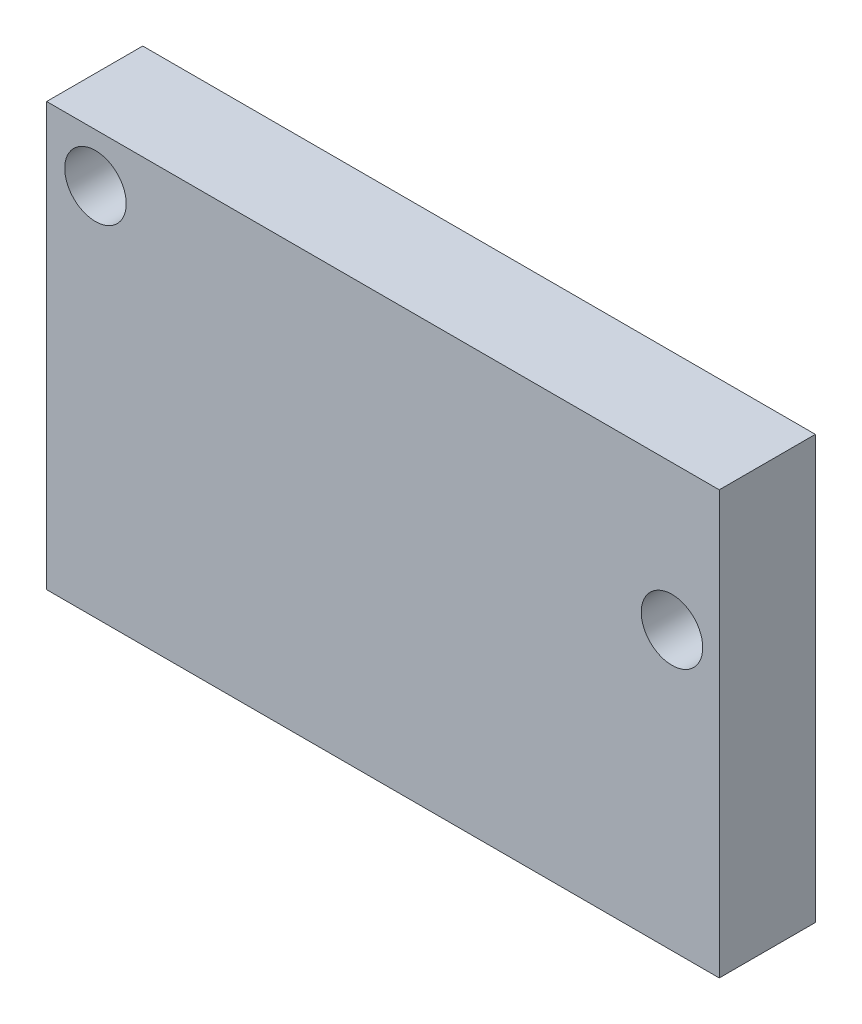
SolidWorks part; units mm, degrees
ref_plane "前视基准面" through (0, 0, 0) normal (0, 0, 1) x (1, 0, 0)
ref_plane "上视基准面" through (0, 0, 0) normal (0, 1, 0) x (1, 0, 0)
ref_plane "右视基准面" through (0, 0, 0) normal (1, 0, 0) x (0, 0, -1)
other "Configuration Table"
sketch "草图1" plane through (0, 0, 0) normal (0, 0, 1) x (1, 0, 0)
  line L1 (0, 0) -> (-35, 0)
  line L2 (0, 0) -> (0, 22)
  line L3 (0, 22) -> (-35, 22)
  line L4 (-35, 0) -> (-35, 22)
  circle A0 centre (-32.46, 19.46) radius 1.6
  circle A1 centre (-2.46, 14.46) radius 1.6
  dimension "D3" = 3.2
  dimension "D5" = 2.54
  dimension "D6" = 3.2
  dimension "D7" = 30
  dimension "D8" = 5
  dimension "D1" = 35
  dimension "D2" = 22
  dimension "D4" = 2.54
extrude "凸台-拉伸1" add sketch "草图1" along normal blind 5
